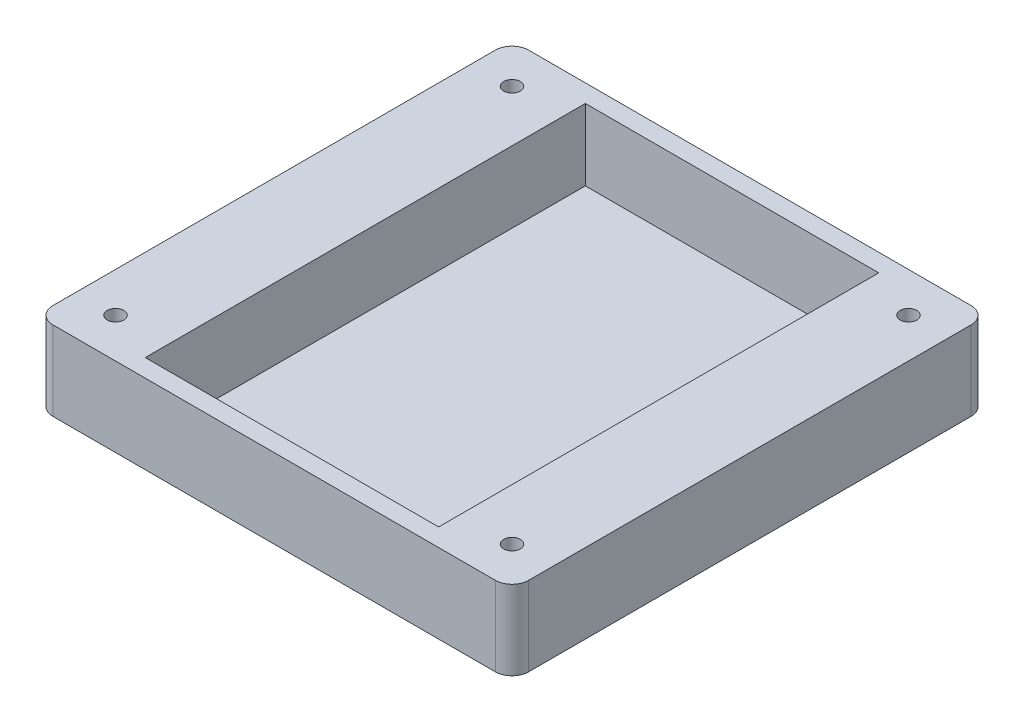
SolidWorks part; units mm, degrees
ref_plane "Front Plane" through (0, 0, 0) normal (0, 0, 1) x (1, 0, 0)
ref_plane "Top Plane" through (0, 0, 0) normal (0, 1, 0) x (1, 0, 0)
ref_plane "Right Plane" through (0, 0, 0) normal (1, 0, 0) x (0, 0, -1)
sketch "Sketch1" plane through (0, 0, 0) normal (0, 1, 0) x (1, 0, 0)
  line L0 (0, 0) -> (0, 26.0698) construction
  line L1 (-55.8, 60) -> (55.8, 60)
  line L2 (-60, 55.8) -> (-60, -55.8)
  line L3 (-55.8, -60) -> (55.8, -60)
  line L4 (60, 55.8) -> (60, -55.8)
  line L5 (-60, 60) -> (60, -60) construction
  line L6 (-60, -60) -> (60, 60) construction
  line L7 (-50, 50) -> (50, 50) construction
  line L8 (-50, 50) -> (-50, -50) construction
  line L9 (-50, -50) -> (50, -50) construction
  line L10 (50, 50) -> (50, -50) construction
  line L11 (-50, 50) -> (50, -50) construction
  line L12 (-50, -50) -> (50, 50) construction
  line L13 (0, 0) -> (27.008, 0) construction
  circle A0 centre (50, 50) radius 2.1
  circle A1 centre (-50, 50) radius 2.1
  circle A2 centre (50, -50) radius 2.1
  circle A3 centre (-50, -50) radius 2.1
  arc A4 (60, -55.8) -> (55.8, -60) centre (55.8, -55.8) cw
  arc A5 (-60, -55.8) -> (-55.8, -60) centre (-55.8, -55.8) ccw
  arc A6 (60, 55.8) -> (55.8, 60) centre (55.8, 55.8) ccw
  arc A7 (-60, 55.8) -> (-55.8, 60) centre (-55.8, 55.8) cw
  point P0 (0, 0)
  point P5 (0, 0)
  dimension "D4" = 4.2
  dimension "D5" = 4.2
  dimension "D1" = 120
  dimension "D2" = 120
  dimension "D3" = 100
extrude "Boss-Extrude1" add sketch "Sketch1" along normal blind 20
sketch "Sketch2" plane through (0, 20, 0) normal (0, 1, 0) x (1, 0, 0)
  line L1 (-37, 55.5) -> (37, 55.5)
  line L2 (-37, 55.5) -> (-37, -55.5)
  line L3 (-37, -55.5) -> (37, -55.5)
  line L4 (37, 55.5) -> (37, -55.5)
  line L5 (-37, 55.5) -> (37, -55.5) construction
  line L6 (-37, -55.5) -> (37, 55.5) construction
  point P0 (0, 0)
  dimension "D1" = 111
  dimension "D2" = 74
extrude "Cut-Extrude1" cut sketch "Sketch2" against normal blind 18
